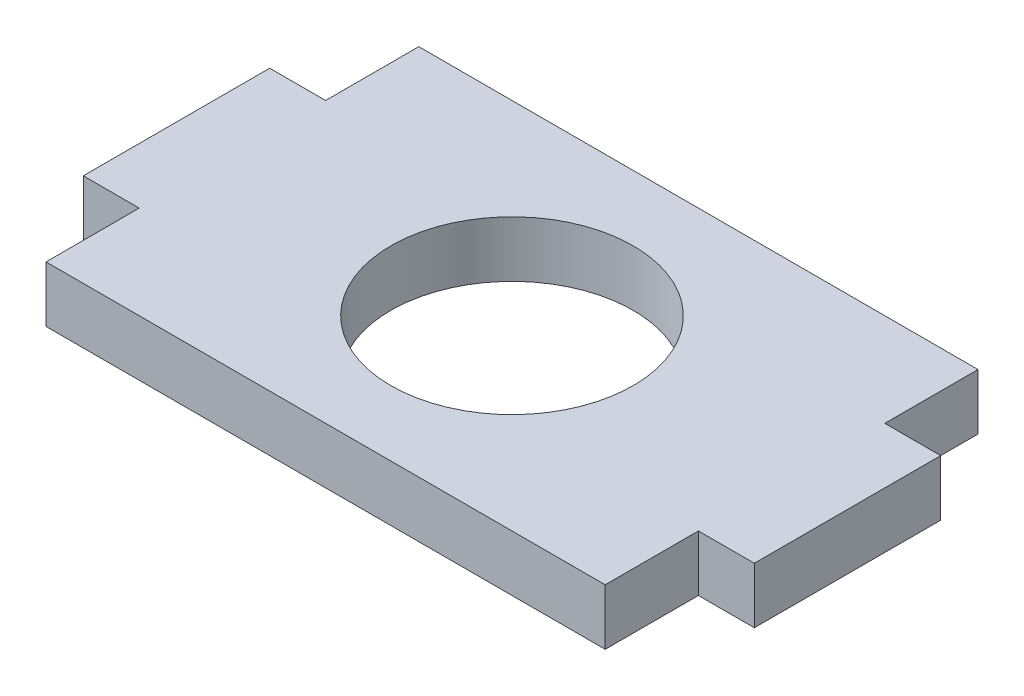
SolidWorks part; units mm, degrees
ref_plane "Alzado" through (0, 0, 0) normal (0, 0, 1) x (1, 0, 0)
ref_plane "Planta" through (0, 0, 0) normal (0, 1, 0) x (1, 0, 0)
ref_plane "Vista lateral" through (0, 0, 0) normal (1, 0, 0) x (0, 0, -1)
sketch "Croquis1" plane through (0, 0, 0) normal (0, 1, 0) x (1, 0, 0)
  line L0 (0, -5) -> (0, 5)
  line L1 (0, 5) -> (3, 5)
  line L2 (3, 5) -> (3, 10)
  line L3 (3, 10) -> (33, 10)
  line L5 (33, 5) -> (33, 10)
  line L6 (36, 5) -> (33, 5)
  line L7 (36, -5) -> (36, 5)
  line L9 (36, -5) -> (33, -5)
  line L10 (33, -5) -> (33, -10)
  line L12 (3, -10) -> (33, -10)
  line L13 (3, -5) -> (3, -10)
  line L14 (0, -5) -> (3, -5)
  circle A0 centre (18, 0) radius 6.5
  point P13 (36, 0)
  dimension "D1" = 13
  dimension "D2" = 3
  dimension "D3" = 5
  dimension "D4" = 30
extrude "Saliente-Extruir1" add sketch "Croquis1" along normal blind 3
